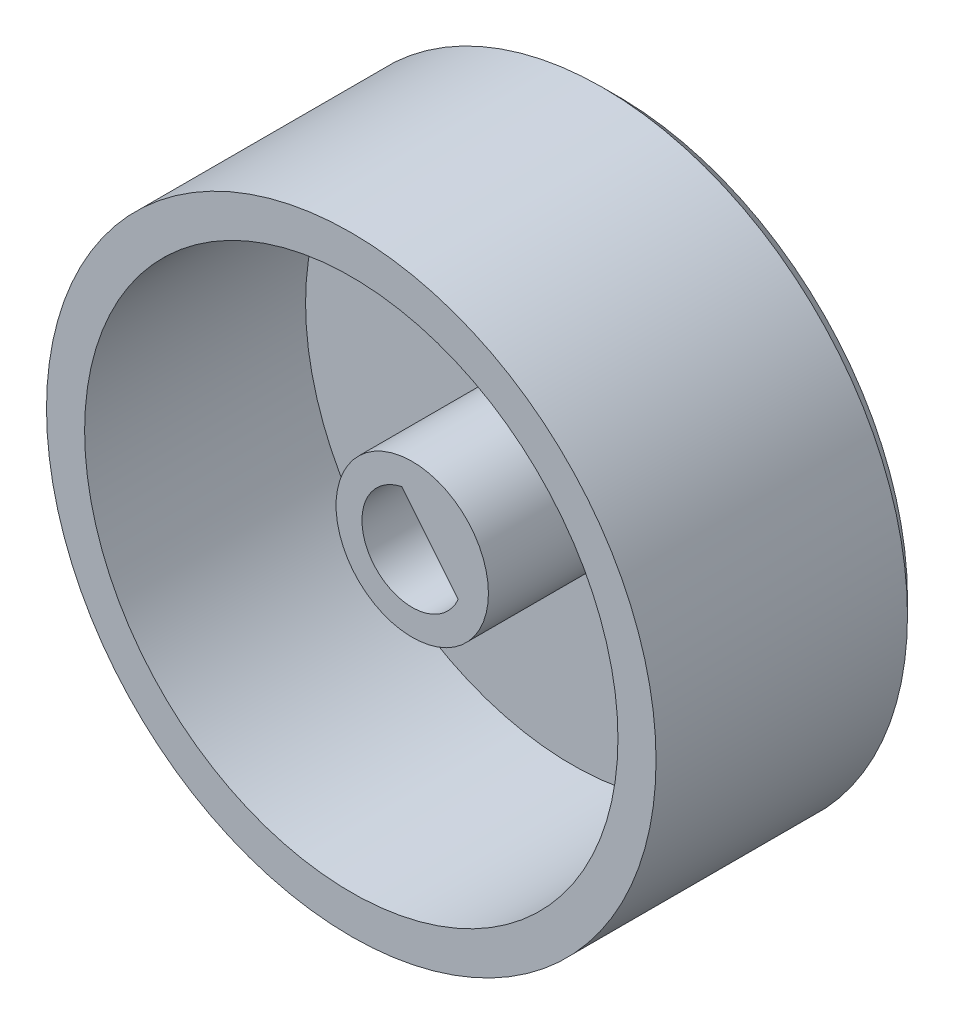
SolidWorks part; units mm, degrees
ref_plane "Front Plane" through (0, 0, 0) normal (0, 0, 1) x (1, 0, 0)
ref_plane "Top Plane" through (0, 0, 0) normal (0, 1, 0) x (1, 0, 0)
ref_plane "Right Plane" through (0, 0, 0) normal (1, 0, 0) x (0, 0, -1)
sketch "Sketch1" plane through (0, 0, 0) normal (0, 0, 1) x (1, 0, 0)
  circle A0 centre (0, 0) radius 20
  dimension "D1" = 40
extrude "Boss-Extrude1" add sketch "Sketch1" along normal blind 15
sketch "Sketch2" plane through (0, 0, 15) normal (0, 0, 1) x (1, 0, 0)
  circle A0 centre (0, 0) radius 17.5
  circle A1 centre (0, 0) radius 5
  circle A2 centre (0, 0) radius 20 construction
  dimension "D1" = 2.5
  dimension "D2" = 10
extrude "Cut-Extrude1" cut sketch "Sketch2" against normal blind 12
sketch "Sketch3" plane through (0, 0, 15) normal (0, 0, 1) x (1, 0, 0)
  line L0 (-0.6826, 3.2286) -> (3.0149, -1.3417)
  arc A0 (-0.6826, 3.2286) -> (3.0149, -1.3417) centre (0, 0) ccw
  dimension "D1" = 3.3
  dimension "D2" = 1.5
extrude "Cut-Extrude2" cut sketch "Sketch3" against normal blind 10.5
sketch "Sketch4" plane through (0, 0, 15) normal (0, 0, 1) x (1, 0, 0)
  circle A0 centre (0, 0) radius 5
extrude "Cut-Extrude3" cut sketch "Sketch4" against normal blind 1.5
chamfer "Chamfer1" distance 1 angle 45 1 edges at (20, 0, 0)
sketch "Sketch7" plane through (0, 0, 15) normal (0, 0, 1) x (1, 0, 0)
  circle A0 centre (0, 0) radius 17.5 construction
  circle A1 centre (0, 0) radius 20
  circle A2 centre (0, 0) radius 20
  circle A3 centre (0, 0) radius 17.5
  dimension "D1" = 0
extrude "Boss-Extrude2" add sketch "Sketch7" along normal blind 2.5
